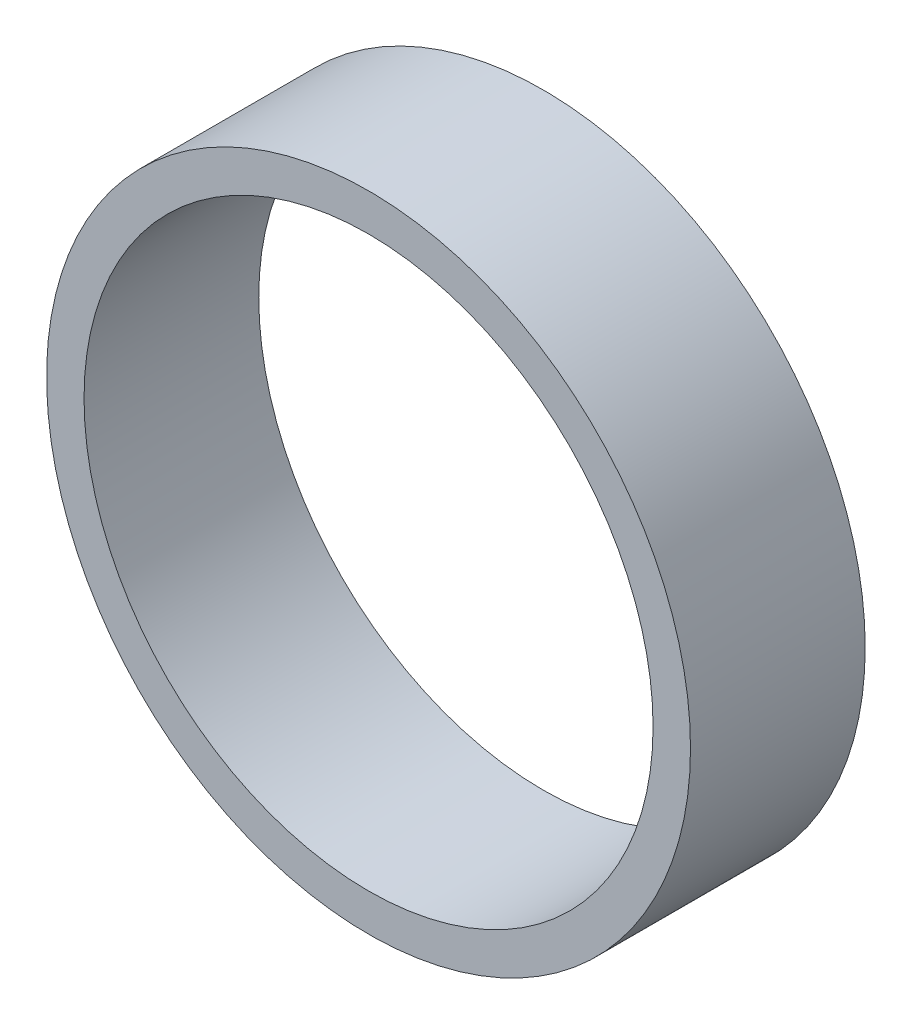
SolidWorks part; units mm, degrees
ref_plane "Front Plane" through (0, 0, 0) normal (0, 0, 1) x (1, 0, 0)
ref_plane "Top Plane" through (0, 0, 0) normal (0, 1, 0) x (1, 0, 0)
ref_plane "Right Plane" through (0, 0, 0) normal (1, 0, 0) x (0, 0, -1)
sketch "Sketch1" plane through (0, 0, 0) normal (0, 0, 1) x (1, 0, 0)
  circle A0 centre (0, 0) radius 6.45
  circle A1 centre (0, 0) radius 5.7
extrude "Ring_Envelope" add sketch "Sketch1" along normal blind 3.5
